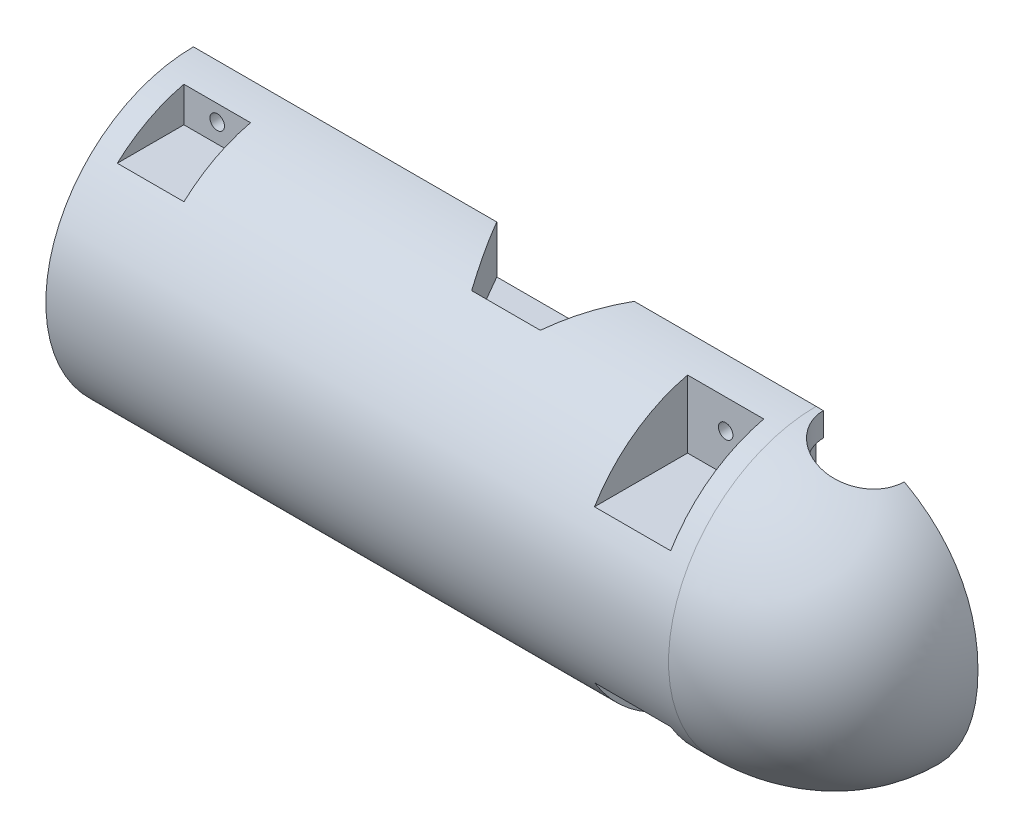
SolidWorks part; units mm, degrees
material "ABS"
ref_plane "Front Plane" through (0, 0, 0) normal (0, 0, 1) x (1, 0, 0)
ref_plane "Top Plane" through (0, 0, 0) normal (0, 1, 0) x (1, 0, 0)
ref_plane "Right Plane" through (0, 0, 0) normal (1, 0, 0) x (0, 0, -1)
sketch "Sketch1" plane through (0, 0, 0) normal (0, 0, 1) x (1, 0, 0)
  line L0 (-52.9373, 0) -> (191.3577, 0) construction
  line L9 (71.5183, 31) -> (136.2706, 31) construction
  line L30 (6.2183, 14) -> (6.2183, 6)
  line L31 (-10.1714, 24.7314) -> (-27.7817, 24.7314)
  line L44 (-56.9817, 31) -> (71.5183, 31)
  line L46 (136.2706, 31) -> (136.2706, 26) construction
  line L47 (136.2706, 26) -> (71.5183, 26) construction
  line L50 (-56.9817, 31) -> (-59.2817, 31)
  line L52 (-59.2817, 31) -> (-59.2817, 24.7314)
  line L54 (71.5183, 13) -> (71.5183, 26) construction
  line L58 (6.2183, 14) -> (71.5183, 14)
  line L78 (71.5183, 14) -> (71.5183, 26)
  line L80 (105.5183, 0) -> (105.5183, 50.2797) construction
  line L81 (100.5183, 0) -> (100.5183, 50.2797) construction
  line L82 (100.5183, 0) -> (105.5183, 0)
  line L83 (3.7183, 24.7314) -> (3.7183, 6)
  line L84 (3.7183, 6) -> (6.2183, 6)
  line L86 (-10.1714, 24.7314) -> (3.7183, 24.7314)
  line L89 (-27.7817, 24.7314) -> (-27.7817, 26.5545)
  line L90 (-27.7817, 26.5545) -> (-35.2817, 26.5545)
  line L91 (-35.2817, 26.5545) -> (-35.2817, 24.7314)
  line L92 (-35.2817, 24.7314) -> (-38.2817, 24.7314)
  line L95 (-38.2817, 21.5343) -> (-38.2817, 24.7314)
  line L96 (-59.2817, 24.7314) -> (-59.2817, 20.4164)
  line L97 (-59.2817, 20.4164) -> (-38.2817, 21.5343)
  spline S0 degree 3 poles (71.5183, 31) (87.3369, 31) (105.5183, 21.7717) (105.5183, 0) knots 0 0 0 0 1 1 1 1
  spline S1 degree 3 poles (71.5183, 26) (84.5012, 26) (100.5183, 18.46) (100.5183, 0) knots 0 0 0 0 1 1 1 1
  dimension "D2" = 5
  dimension "D3" = 0
  dimension "D4" = 6
  dimension "D5" = 0
  dimension "D6" = 34
  dimension "D7" = 7.5
  dimension "D8" = 2.5
  dimension "D9" = 3
  dimension "D10" = 14
revolve "Revolve1" add sketch "Sketch1" angle 180 about L0
ref_plane "Plane4" through (0, 0, 7) normal (0, 0, -1) x (-1, 0, 0)
sketch "Sketch2" plane through (0, 0, 7) normal (0, 0, -1) x (-1, 0, 0)
  line L10 (40.2817, 31) -> (40.2817, 22.8142)
  line L11 (40.2817, 22.8142) -> (54.2817, 22.8142)
  line L12 (54.2817, 22.8142) -> (54.2817, 31)
  line L13 (-51.5183, -31) -> (-51.5183, -16)
  line L15 (-67.5183, -16) -> (-51.5183, -16)
  line L20 (-71.5183, -31) -> (59.2817, -31) construction
  line L21 (-6.2183, -14) -> (-71.5183, -14) construction
  line L23 (40.2817, 31) -> (54.2817, 31)
  line L24 (-67.5183, 16) -> (-67.5183, 31)
  line L37 (-71.5183, 31) -> (59.2817, 31) construction
  line L38 (-67.5183, 31) -> (-51.5183, 31)
  line L39 (-120.0889, 0) -> (106.8977, 0) construction
  line L41 (40.2817, -31) -> (54.2817, -31)
  line L43 (54.2817, -22.8142) -> (54.2817, -31)
  line L44 (40.2817, -22.8142) -> (54.2817, -22.8142)
  line L45 (40.2817, -31) -> (40.2817, -22.8142)
  line L56 (-67.5183, 16) -> (-51.5183, 16)
  line L58 (-67.5183, -31) -> (-51.5183, -31)
  line L59 (-67.5183, -16) -> (-67.5183, -31)
  line L60 (-51.5183, 31) -> (-51.5183, 16)
  line L62 (38.2817, 21.5343) -> (38.2817, 24.7314) construction
  point P23 (-59.5183, -24)
  point P35 (-59.5183, 24)
  dimension "D2" = 16
  dimension "D3" = 2
  dimension "D4" = 14
  dimension "D5" = 16
  dimension "D6" = 8
  dimension "D7" = 2
extrude "Cut-Extrude1" cut sketch "Sketch2" against normal up to next
sketch "Sketch3" plane through (0, 0, 7) normal (0, 0, 1) x (1, 0, 0)
  line L0 (-54.2817, 22.8142) -> (-54.2817, 30.1993) construction
  line L1 (-40.2817, 22.8142) -> (-54.2817, 22.8142) construction
  line L13 (55, 0) -> (-55, 0) construction
  circle A0 centre (-47.2817, 26.8142) radius 1.525
  circle A4 centre (-47.2817, -26.8142) radius 1.525
  circle A7 centre (59.5183, 24) radius 1.525
  circle A8 centre (59.5183, -24) radius 1.525
  dimension "D1" = 3.05
  dimension "D2" = 7
  dimension "D3" = 3.05
  dimension "D4" = 4
  dimension "D6" = 59.5183
  dimension "D5" = 3.05
  dimension "D7" = 24
  dimension "D8" = 24
  dimension "D9" = 59.5183
extrude "Cut-Extrude2" cut sketch "Sketch3" against normal up to next
ref_plane "Plane5" through (0, 31, 0) normal (0, 1, 0) x (1, 0, 0)
sketch "Sketch5" plane through (0, 31, 0) normal (0, 1, 0) x (1, 0, 0)
  line L3 (4.4419, 0) -> (11.6588, -12.5)
  line L4 (11.6588, -12.5) -> (26.0926, -12.5)
  line L5 (26.0926, -12.5) -> (33.3095, 0)
  line L6 (33.3095, 0) -> (26.0926, 12.5)
  line L7 (26.0926, 12.5) -> (11.6588, 12.5)
  line L8 (11.6588, 12.5) -> (4.4419, 0)
  circle A0 centre (18.8757, 0) radius 12.5 construction
  dimension "D1" = 25
extrude "Cut-Extrude3" cut sketch "Sketch5" against normal blind 10
sketch "Sketch6" plane through (0, 31, 0) normal (0, 1, 0) x (1, 0, 0)
  line L2 (71.5183, -31) -> (71.5183, 0) construction
  circle A0 centre (81.5183, 0) radius 8.5
  dimension "D1" = 17
  dimension "D2" = 10
extrude "Cut-Extrude4" cut sketch "Sketch6" against normal up to next
